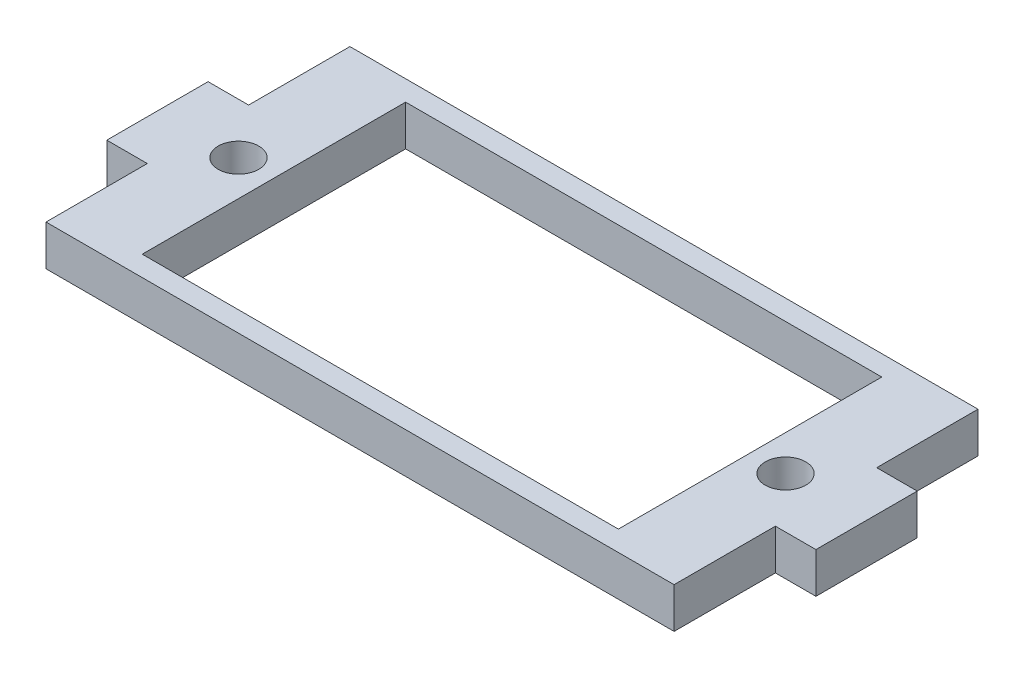
SolidWorks part; units mm, degrees
material "Acrylic (Medium-high impact)"
ref_plane "Front Plane" through (0, 0, 0) normal (0, 0, 1) x (1, 0, 0)
ref_plane "Top Plane" through (0, 0, 0) normal (0, 1, 0) x (1, 0, 0)
ref_plane "Right Plane" through (0, 0, 0) normal (1, 0, 0) x (0, 0, -1)
sketch "Sketch1" plane through (0, 0, 0) normal (0, 1, 0) x (1, 0, 0)
  line L0 (0, 5.0919) -> (0, -9.9447) construction
  line L1 (17.5, -7.5) -> (-17.5, -7.5)
  line L2 (17.5, -7.5) -> (17.5, 7.5)
  line L3 (17.5, 7.5) -> (-17.5, 7.5)
  line L4 (-17.5, -7.5) -> (-17.5, 7.5)
  line L5 (17.5, -7.5) -> (-17.5, 7.5) construction
  line L6 (17.5, 7.5) -> (-17.5, -7.5) construction
  line L7 (11.75, -6.5) -> (-11.75, -6.5)
  line L8 (11.75, -6.5) -> (11.75, 6.5)
  line L9 (11.75, 6.5) -> (-11.75, 6.5)
  line L10 (-11.75, -6.5) -> (-11.75, 6.5)
  line L11 (11.75, -6.5) -> (-11.75, 6.5) construction
  line L12 (11.75, 6.5) -> (-11.75, -6.5) construction
  circle A0 centre (-13.5, 0) radius 1
  circle A1 centre (13.5, 0) radius 1
  point P0 (0, 0)
  point P6 (0, 0)
  dimension "D5" = 2
  dimension "D1" = 35
  dimension "D2" = 15
  dimension "D3" = 23.5
  dimension "D4" = 13
  dimension "D6" = 1.75
  dimension "D7" = 7.5
extrude "Boss-Extrude1" add sketch "Sketch1" along normal blind 2
sketch "Sketch2" plane through (0, 2, 0) normal (0, 1, 0) x (1, 0, 0)
  line L0 (17.5, 7.5) -> (-17.5, 7.5) construction
  line L1 (17.5, 7.5) -> (15.5, 7.5)
  line L2 (17.5, 7.5) -> (17.5, 2.5)
  line L3 (17.5, 2.5) -> (15.5, 2.5)
  line L4 (15.5, 7.5) -> (15.5, 2.5)
  line L5 (17.5, -7.5) -> (17.5, 7.5) construction
  line L6 (17.5, 0) -> (-19.0519, 0) construction
  line L7 (0, 7.5) -> (0, -9.5533) construction
  line L8 (17.5, -2.5) -> (15.5, -2.5)
  line L9 (17.5, -7.5) -> (17.5, -2.5)
  line L10 (17.5, -7.5) -> (15.5, -7.5)
  line L11 (15.5, -7.5) -> (15.5, -2.5)
  line L12 (-17.5, -7.5) -> (-15.5, -7.5)
  line L13 (-15.5, -7.5) -> (-15.5, -2.5)
  line L14 (-17.5, -7.5) -> (-17.5, -2.5)
  line L15 (-17.5, -2.5) -> (-15.5, -2.5)
  line L16 (-17.5, 7.5) -> (-17.5, 2.5)
  line L17 (-17.5, 7.5) -> (-15.5, 7.5)
  line L18 (-15.5, 7.5) -> (-15.5, 2.5)
  line L19 (-17.5, 2.5) -> (-15.5, 2.5)
  dimension "D1" = 5
  dimension "D2" = 2
extrude "Cut-Extrude1" cut sketch "Sketch2" against normal blind 2
